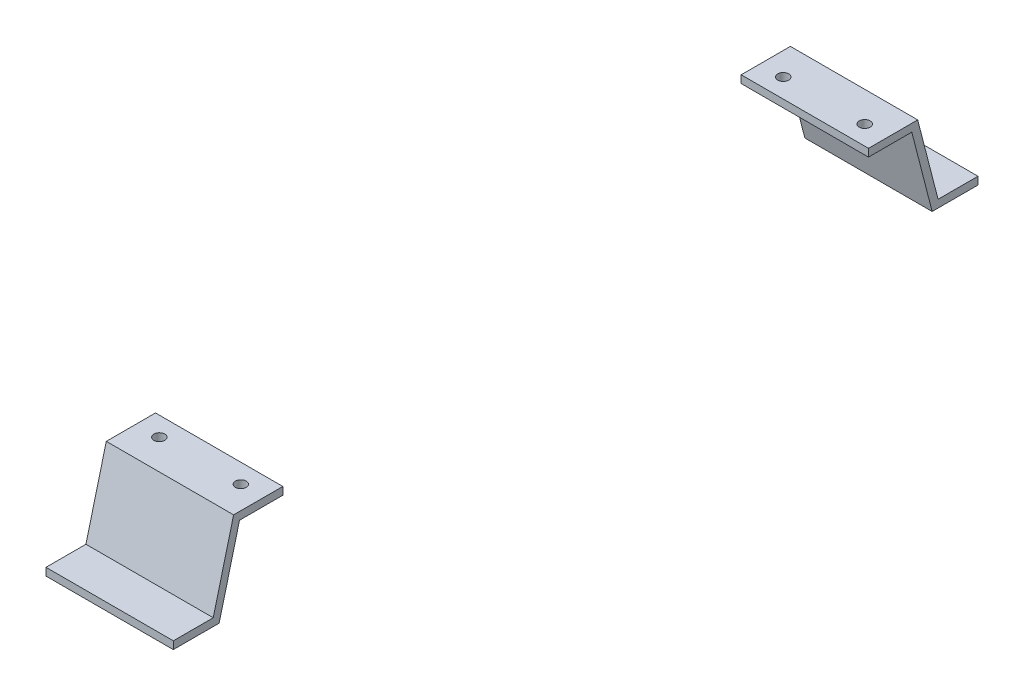
SolidWorks part; units mm, degrees
ref_plane "前视基准面" through (0, 0, 0) normal (0, 0, 1) x (1, 0, 0)
ref_plane "上视基准面" through (0, 0, 0) normal (0, 1, 0) x (1, 0, 0)
ref_plane "右视基准面" through (0, 0, 0) normal (1, 0, 0) x (0, 0, -1)
sketch "草图1" plane through (0, 0, 0) normal (1, 0, 0) x (0, 0, -1)
  line L0 (-158, 132) -> (-140, 132)
  line L3 (-140, 132) -> (-132, 163)
  line L4 (-132, 163) -> (-115, 163)
  line L5 (0, 0) -> (0, 291.0657) construction
  line L6 (132, 163) -> (115, 163) construction
  line L7 (140, 132) -> (132, 163) construction
  line L8 (158, 132) -> (140, 132) construction
  dimension "D1" = 230
  dimension "D2" = 17
  dimension "D3" = 31
  dimension "D4" = 18
  dimension "D5" = 280
extrude "拉伸-薄壁1" add sketch "草图1" along normal mid plane 50 thin thin type one direction reverse wall 3
hole_wizard "M4 间隙孔2" positions "草图5" profile "草图4" hole size "M4" standard "GB" end condition up to next
sketch "草图5" plane through (0, 166, 0) normal (0, 1, 0) x (1, 0, 0)
  line L0 (0, -115) -> (0, -134.3241) construction
  line L1 (25, -115) -> (-25, -115) construction
  line L2 (25, -134.3241) -> (-25, -134.3241) construction
  line L4 (0, 0) -> (-32.576, 0) construction
  point P0 (16, -122.5)
  point P2 (-16, -122.5)
  dimension "D1" = 32
  dimension "D2" = 245
sketch "草图4" plane through (16, 166, 122.5) normal (1, 0, 0) x (0, 0, 1)
  line L0 (0, 0) -> (0, 3)
  line L1 (0, 3) -> (2.15, 3)
  line L2 (2.15, 3) -> (2.15, 0)
  line L5 (2.15, 0) -> (0, 0)
  line L11 (0, -6.35) -> (0, 107.95) construction
  dimension "通孔孔直径" = 4.3
  dimension "通孔孔深度" = 3
mirror "镜向2" about plane through (0, 0, 0) normal (0, 0, 1) of bodies 108
